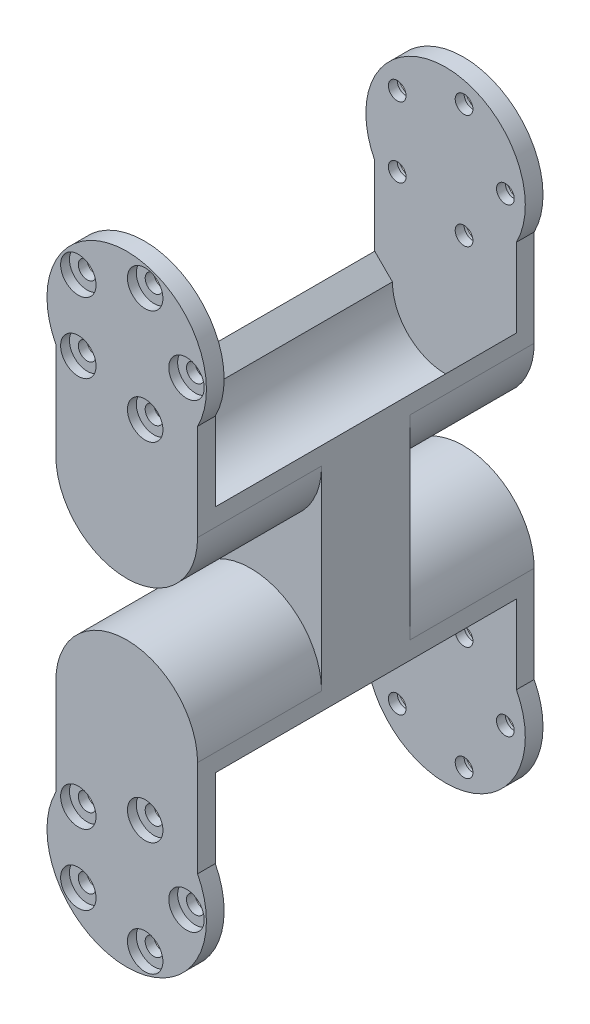
SolidWorks part; units mm, degrees
ref_plane "Front Plane" through (0, 0, 0) normal (0, 0, 1) x (1, 0, 0)
ref_plane "Top Plane" through (0, 0, 0) normal (0, 1, 0) x (1, 0, 0)
ref_plane "Right Plane" through (0, 0, 0) normal (1, 0, 0) x (0, 0, -1)
sketch "Sketch2" plane through (0, 0, 0) normal (0, 0, 1) x (1, 0, 0)
  line L2 (-16, 0) -> (-16, 30)
  line L4 (16, 0) -> (16, 30)
  circle A0 centre (0, 0) radius 11 construction
  arc A1 (-16, 0) -> (16, 0) centre (0, 0) ccw
  arc A2 (16, 30) -> (-16, 30) centre (0, 30) ccw
  dimension "D1" = 32
  dimension "D2" = 5
  dimension "D3" = 30
extrude "Boss-Extrude2" add sketch "Sketch2" along normal blind 4
sketch "Sketch3" plane through (0, 0, 0) normal (0, 0, -1) x (-1, 0, 0)
  line L2 (-16, 30) -> (-16, 26)
  line L3 (-16, 0) -> (-16, 30) construction
  line L4 (-16, 26) -> (-12, 30)
  line L5 (16, 30) -> (16, 26)
  line L6 (16, 30) -> (16, 0) construction
  line L7 (16, 26) -> (12, 30)
  arc A0 (16, 30) -> (-16, 30) centre (0, 30) ccw
  arc A1 (12, 30) -> (-12, 30) centre (0, 30) ccw
  dimension "D1" = 4
  dimension "D2" = 4
  dimension "D3" = 4
extrude "Boss-Extrude3" add sketch "Sketch3" along normal blind 68
sketch "Sketch4" plane through (0, 0, -68) normal (0, 0, -1) x (-1, 0, 0)
  line L0 (-16, 30) -> (-16, 0)
  line L1 (16, 30) -> (16, 0)
  arc A0 (16, 30) -> (-16, 30) centre (0, 30) ccw
  arc A1 (-16, 0) -> (16, 0) centre (0, 0) ccw
  circle A2 centre (0, 0) radius 10 construction
extrude "Boss-Extrude4" add sketch "Sketch4" along normal blind 4
sketch "Sketch5" plane through (0, 0, 4) normal (0, 0, 1) x (1, 0, 0)
  line L0 (-16, 60) -> (16, 60) construction
  line L1 (-16, 0) -> (-10, 0)
  line L2 (-16, 0) -> (-16, 120)
  line L3 (-16, 120) -> (16, 120)
  line L4 (16, 0) -> (16, 120)
  line L5 (10, 0) -> (16, 0)
  circle A0 centre (0, 0) radius 10
  dimension "D1" = 120
  dimension "D2" = 32
extrude "Boss-Extrude5" add sketch "Sketch5" against normal blind 4
ref_plane "Plane1" through (0, -16, 0) normal (0, -1, 0) x (-1, 0, 0)
ref_plane "Plane2" through (0, 52, 0) normal (0, -1, 0) x (-1, 0, 0)
mirror "Mirror3" about plane through (0, 52, 0) normal (0, -1, 0) of "Boss-Extrude4", "Boss-Extrude3", "Boss-Extrude2"
ref_plane "Plane3" through (0, 0, -34) normal (0, 0, 1) x (1, 0, 0)
sketch "Sketch6" plane through (0, 0, 4) normal (0, 0, 1) x (1, 0, 0)
  line L0 (-16, 120) -> (16, 120) construction
  line L2 (16, 120) -> (-16, 120)
  line L3 (16, 120) -> (16, 104)
  line L5 (-16, 120) -> (-16, 104)
  arc A0 (16, 104) -> (-16, 104) centre (0, 104) ccw
  line M2 (16, 0) -> (16, 120)
  line M3 (16, 120) -> (-16, 120)
  line M4 (-16, 120) -> (-16, 0)
extrude "Cut-Extrude1" cut sketch "Sketch6" against normal up to next contours A0 L2 M4 | A0 M2 M3
mirror "Mirror4" about plane through (0, 0, -34) normal (0, 0, 1) of "Boss-Extrude5", "Cut-Extrude1"
sketch "Sketch8" plane through (0, 0, -72) normal (0, 0, -1) x (-1, 0, 0)
  line L0 (-16, 74) -> (-16, 30)
  line L2 (16, 30) -> (16, 74)
  arc A0 (-16, 74) -> (16, 74) centre (0, 74) ccw
  arc A1 (16, 30) -> (-16, 30) centre (0, 30) ccw
extrude "Cut-Extrude2" cut sketch "Sketch8" against normal through all
ref_plane "Plane4" through (0, 0, 0) normal (-1, 0, 0) x (0, 0, 1)
sketch "Sketch9" plane through (0, 0, -34) normal (0, 0, 1) x (1, 0, 0)
  line L2 (-16, 74) -> (-16, 30)
  line L4 (16, 74) -> (16, 30)
  arc A0 (-16, 74) -> (16, 74) centre (0, 74) ccw
  arc A1 (16, 30) -> (-16, 30) centre (0, 30) ccw
extrude "Boss-Extrude7" add sketch "Sketch9" along normal blind 10 and the other way blind 10
sketch "Sketch10" plane through (0, 0, -72) normal (0, 0, -1) x (-1, 0, 0)
  circle A2 centre (-13.5, 0) radius 2
  circle A3 centre (-4.1717, 12.8393) radius 2
  circle A4 centre (10.9217, 7.9351) radius 2
  circle A5 centre (10.9217, -7.9351) radius 2
  circle A6 centre (-4.1717, -12.8393) radius 2
  point P17 (0, 0)
  dimension "D2" = 4
  dimension "D3" = 5
extrude "Cut-Extrude3" cut sketch "Sketch10" against normal blind 4
sketch "Sketch11" plane through (0, 0, -72) normal (0, 0, -1) x (-1, 0, 0)
  circle A0 centre (0, 0) radius 16
  circle A1 centre (0, 0) radius 18
  dimension "D1" = 2
extrude "Boss-Extrude8" add sketch "Sketch11" against normal blind 4
mirror "Mirror5" about plane through (0, 0, -34) normal (0, 0, 1) of "Boss-Extrude8", "Cut-Extrude3"
mirror "Mirror6" about plane through (0, 52, 0) normal (0, -1, 0) of "Mirror5", "Cut-Extrude3", "Boss-Extrude8"
sketch "Sketch12" plane through (0, 0, 4) normal (0, 0, 1) x (1, 0, 0)
  circle A16 centre (-10.9217, 7.9351) radius 2
  circle A17 centre (-10.9217, 7.9351) radius 4.0002
  circle A18 centre (4.1717, 12.8393) radius 4.0002
  circle A19 centre (4.1717, 12.8393) radius 2
  circle A20 centre (13.5, 0) radius 4.0002
  circle A21 centre (13.5, 0) radius 2
  circle A22 centre (4.1717, -12.8393) radius 4.0002
  circle A23 centre (4.1717, -12.8393) radius 2
  circle A24 centre (-10.9217, -7.9351) radius 4.0002
  circle A25 centre (-10.9217, -7.9351) radius 2
  point P22 (0, 0)
  point P30 (0.001, 0)
  dimension "D1" = 5
extrude "Cut-Extrude5" cut sketch "Sketch12" against normal blind 2
mirror "Mirror7" about plane through (0, 0, -34) normal (0, 0, 1) of "Cut-Extrude5"
mirror "Mirror8" about plane through (0, 52, 0) normal (0, -1, 0) of "Cut-Extrude5", "Mirror7"
sketch "Sketch13" plane through (-16, 0, 0) normal (-1, 0, 0) x (0, 0, 1)
  line L0 (-44, 74) -> (-44, 30) construction
  line L1 (-67.7707, 58) -> (-67.7707, 46) construction
  line L2 (-72, 58) -> (-44, 58) construction
  line L3 (-44, 54.5) -> (-40, 54.5)
  line L4 (-44, 54.5) -> (-44, 49.5)
  line L5 (-44, 49.5) -> (-40, 49.5)
  line L6 (-40, 54.5) -> (-40, 49.5)
  line L7 (-24, 74) -> (-24, 30) construction
  line L8 (-24, 54.5) -> (-28, 54.5)
  line L9 (-24, 54.5) -> (-24, 49.5)
  line L10 (-24, 49.5) -> (-28, 49.5)
  line L11 (-28, 54.5) -> (-28, 49.5)
  line L12 (-44, 46) -> (-72, 46) construction
  line L13 (-4.7589, 58) -> (-4.7589, 46) construction
  line L14 (-24, 58) -> (4, 58) construction
  line L15 (4, 46) -> (-24, 46) construction
  point P24 (-67.7707, 52)
  point P25 (-44, 52)
  point P26 (-28, 52)
  dimension "D1" = 4
  dimension "D2" = 4
  dimension "D3" = 5
  dimension "D4" = 5
extrude "Boss-Extrude9" add sketch "Sketch13" along normal blind 6
sketch "Sketch14" plane through (-22, 0, 0) normal (-1, 0, 0) x (0, 0, 1)
  line L1 (-44, 54.5) -> (-24, 54.5)
  line L2 (-44, 54.5) -> (-44, 49.5)
  line L3 (-44, 49.5) -> (-24, 49.5)
  line L4 (-24, 54.5) -> (-24, 49.5)
extrude "Boss-Extrude10" add sketch "Sketch14" along normal blind 4
fillet "Fillet1" radius 5 2 edges at (-26, 52, -44) (-26, 52, -24)
